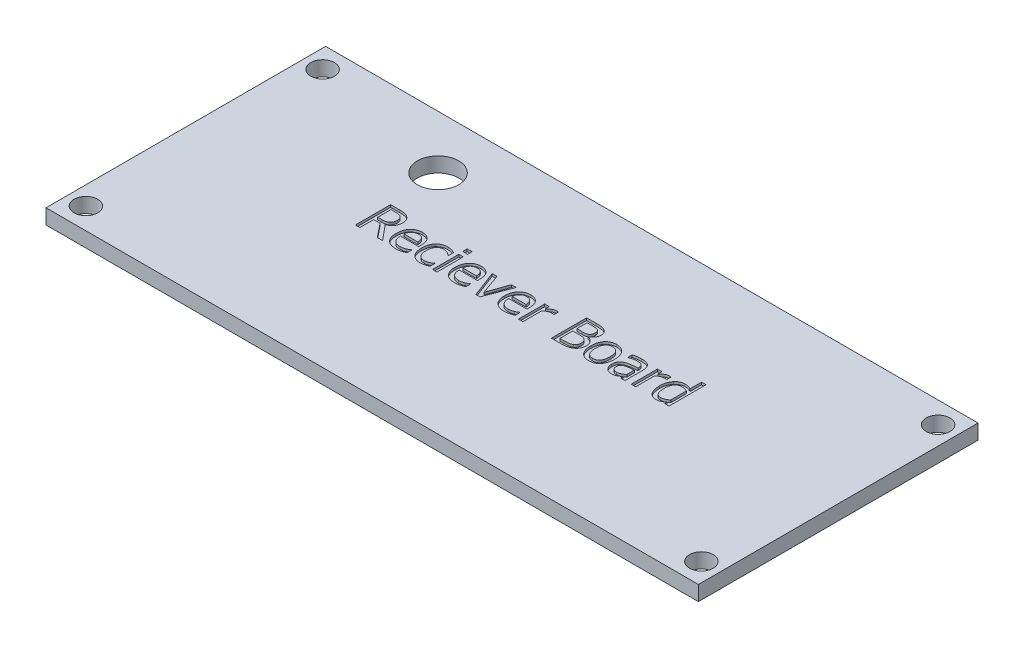
SolidWorks part; units mm, degrees
ref_plane "Front Plane" through (0, 0, 0) normal (0, 0, 1) x (1, 0, 0)
ref_plane "Top Plane" through (0, 0, 0) normal (0, 1, 0) x (1, 0, 0)
ref_plane "Right Plane" through (0, 0, 0) normal (1, 0, 0) x (0, 0, -1)
sketch "Sketch1" plane through (0, 0, 0) normal (0, 1, 0) x (1, 0, 0)
  line L0 (-33.02, 11.43) -> (-33.02, -11.43) construction
  line L1 (-35, -15) -> (35, -15)
  line L2 (-35, -15) -> (-35, 15)
  line L3 (-35, 15) -> (35, 15)
  line L4 (35, -15) -> (35, 15)
  line L5 (-35, -15) -> (35, 15) construction
  line L6 (-35, 15) -> (35, -15) construction
  line L7 (0, 0) -> (-35, 0) construction
  line L9 (0, 0) -> (35, 0) construction
  line L10 (-31.75, -12.7) -> (31.75, -12.7) construction
  circle A0 centre (-33.02, 12.7) radius 1.27
  circle A1 centre (-33.02, -12.7) radius 1.27
  circle A2 centre (33.02, 12.7) radius 1.27
  circle A3 centre (33.02, -12.7) radius 1.27
  point P0 (0, 0)
  point P14 (-33.02, 0)
  point P15 (0, -12.7)
  point P24 (33.02, 0)
  dimension "D3" = 2.54
  dimension "D4" = 2.54
  dimension "D1" = 70
  dimension "D2" = 30
  dimension "D5" = 25.4
  dimension "D6" = 66.04
extrude "Boss-Extrude1" add sketch "Sketch1" along normal blind 1.6
sketch "Sketch2" plane through (0, 1.6, 0) normal (0, 1, 0) x (1, 0, 0)
  line L0 (-35, 0) -> (35, 0) construction
  line L1 (-35, 15) -> (-35, -15) construction
  line L2 (35, -15) -> (35, 15) construction
  text T0 "Reciever Board" font "Tahoma" height in points 14
extrude "Cut-Extrude1" cut sketch "Sketch2" against normal blind 0.254
sketch "Sketch3" plane through (0, 1.6, 0) normal (0, 1, 0) x (1, 0, 0)
  line L2 (-35, 15) -> (-35, -15) construction
  line L3 (35, 15) -> (-35, 15) construction
  circle A0 centre (-17.22, 9.285) radius 2.2225
  dimension "D1" = 4.445
  dimension "D2" = 17.78
  dimension "D3" = 5.715
extrude "Cut-Extrude2" cut sketch "Sketch3" against normal through all
